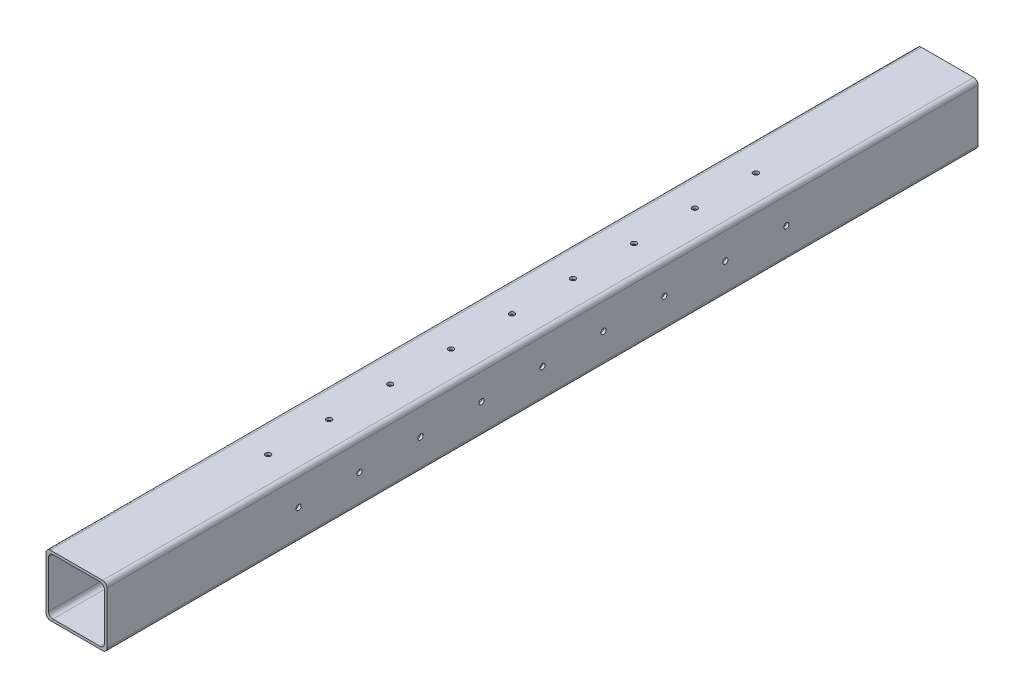
SolidWorks part; units mm, degrees
ref_plane "Front Plane" through (0, 0, 0) normal (0, 0, 1) x (1, 0, 0)
ref_plane "Top Plane" through (0, 0, 0) normal (0, 1, 0) x (1, 0, 0)
ref_plane "Right Plane" through (0, 0, 0) normal (1, 0, 0) x (0, 0, -1)
sketch "Sketch1" plane through (0, 0, 0) normal (0, 0, 1) x (1, 0, 0)
  line L0 (3, 67) -> (67, 67)
  line L1 (0, 0) -> (70, 0)
  line L2 (0, 0) -> (0, 70)
  line L3 (0, 70) -> (70, 70)
  line L4 (70, 0) -> (70, 70)
  line L5 (67, 3) -> (67, 67)
  line L6 (3, 3) -> (67, 3)
  line L7 (3, 3) -> (3, 67)
  dimension "D1" = 70
  dimension "D2" = 70
  dimension "D3" = 3
extrude "Boss-Extrude1" add sketch "Sketch1" along normal blind 1000
fillet "Fillet1" radius 5 8 edges at (67, 67, 500) (0, 70, 500) (0, 0, 500) (67, 3, 500) (70, 0, 500) (3, 3, 500) (3, 67, 500) (70, 70, 500)
sketch "Sketch5" plane through (0, 70, 0) normal (0, 1, 0) x (1, 0, 0)
  line L0 (5, -500) -> (65, -500) construction
  line L1 (5, 0) -> (5, -1000) construction
  line L2 (65, -1000) -> (65, 0) construction
  circle A0 centre (35, -500) radius 3
extrude "Cut-Extrude3" cut sketch "Sketch5" against normal blind 70
pattern_linear "LPattern1" count 5 spacing 70 along (0, 0, 1) count 5 spacing 70 along (0, 0, -1) of "Cut-Extrude3"
sketch "Sketch6" plane through (0, 0, 0) normal (-1, 0, 0) x (0, 0, 1)
  line L0 (500, 65) -> (500, 5) construction
  line L1 (1000, 65) -> (0, 65) construction
  line L2 (0, 5) -> (1000, 5) construction
  circle A0 centre (500, 35) radius 3
extrude "Cut-Extrude4" cut sketch "Sketch6" against normal blind 70
pattern_linear "LPattern2" count 5 spacing 70 along (0, 0, -1) count 5 spacing 70 along (0, 0, 1) of "Cut-Extrude4"
